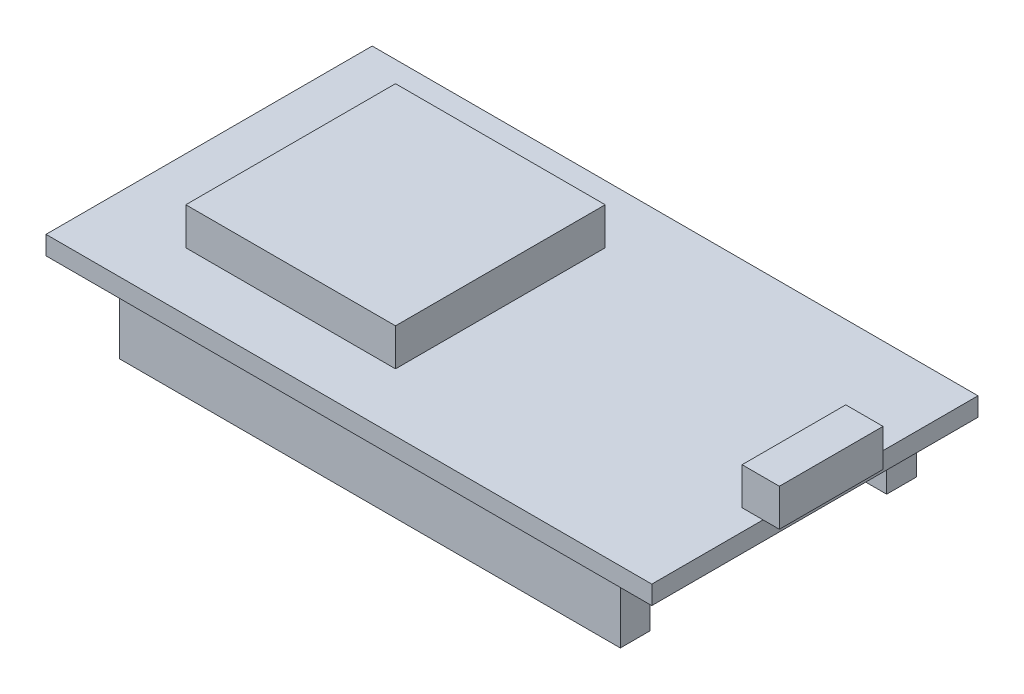
SolidWorks part; units mm, degrees
ref_plane "Front Plane" through (0, 0, 0) normal (0, 0, 1) x (1, 0, 0)
ref_plane "Top Plane" through (0, 0, 0) normal (0, 1, 0) x (1, 0, 0)
ref_plane "Right Plane" through (0, 0, 0) normal (1, 0, 0) x (0, 0, -1)
ref_plane "Plane1" through (0, 9, 0) normal (0, 1, 0) x (1, 0, 0)
sketch "Sketch1" plane through (0, 9, 0) normal (0, 1, 0) x (1, 0, 0)
  line L0 (9, 14) -> (61, 14)
  line L1 (61, 14) -> (61, -14)
  line L2 (61, -14) -> (9, -14)
  line L3 (9, -14) -> (9, 14)
extrude "Boss-Extrude1" add sketch "Sketch1" along normal blind 1.6
ref_plane "Plane2" through (0, 10.6, 0) normal (0, 1, 0) x (1, 0, 0)
sketch "Sketch2" plane through (0, 10.6, 0) normal (0, 1, 0) x (1, 0, 0)
  line L0 (16, 9) -> (34, 9)
  line L1 (34, 9) -> (34, -9)
  line L2 (34, -9) -> (16, -9)
  line L3 (16, -9) -> (16, 9)
extrude "Boss-Extrude2" add sketch "Sketch2" along normal blind 3.2
sketch "Sketch3" plane through (0, 10.6, 0) normal (0, 1, 0) x (1, 0, 0)
  line L0 (59.2, 4.45) -> (62.4, 4.45)
  line L1 (62.4, 4.45) -> (62.4, -4.45)
  line L2 (62.4, -4.45) -> (59.2, -4.45)
  line L3 (59.2, -4.45) -> (59.2, 4.45)
extrude "Boss-Extrude3" add sketch "Sketch3" along normal blind 3.2
sketch "Sketch4" plane through (0, 9, 0) normal (0, 1, 0) x (1, 0, 0)
  line L0 (14, 12.7) -> (57, 12.7)
  line L1 (57, 12.7) -> (57, 10.16)
  line L2 (57, 10.16) -> (14, 10.16)
  line L3 (14, 10.16) -> (14, 12.7)
  line L4 (14, -10.16) -> (57, -10.16)
  line L5 (57, -10.16) -> (57, -12.7)
  line L6 (57, -12.7) -> (14, -12.7)
  line L7 (14, -12.7) -> (14, -10.16)
extrude "Boss-Extrude4" add sketch "Sketch4" against normal blind 5.8
